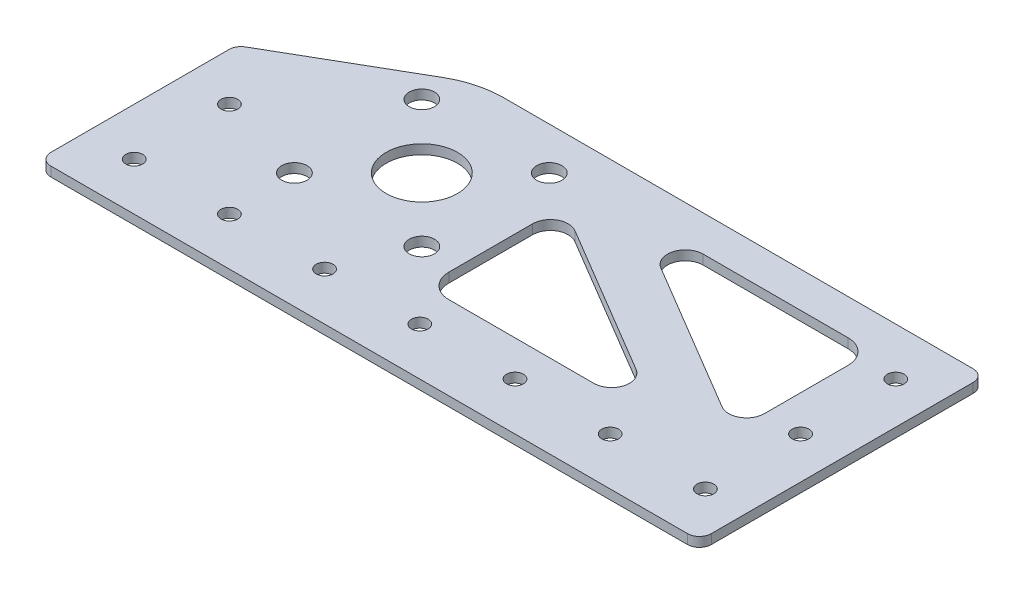
SolidWorks part; units mm, degrees
material "6061-O (SS)"
ref_plane "Front Plane" through (0, 0, 0) normal (0, 0, 1) x (1, 0, 0)
ref_plane "Top Plane" through (0, 0, 0) normal (0, 1, 0) x (1, 0, 0)
ref_plane "Right Plane" through (0, 0, 0) normal (1, 0, 0) x (0, 0, -1)
sketch "Sketch1" plane through (0, 0, 0) normal (0, 1, 0) x (1, 0, 0)
  line L2 (0, 50.7261) -> (0, 3.175)
  line L3 (3.175, 0) -> (173.0375, 0)
  line L4 (176.2125, 73.025) -> (176.2125, 3.175)
  line L8 (173.0375, 76.2) -> (47.7531, 76.2)
  line L13 (0, 787.4) -> (0, 25.4) construction
  line L14 (-76.2, 0) -> (609.6, 0) construction
  line L18 (177.8, 787.4) -> (177.8, 25.4) construction
  line L19 (1.5875, 53.4757) -> (35.0531, 72.797)
  arc A3 (165.0238, 65.5687) -> (165.0238, 61.4313) centre (165.1, 63.5) ccw construction
  arc A4 (0, 3.175) -> (3.175, 0) centre (3.175, 3.175) ccw
  arc A5 (1.5875, 53.4757) -> (0, 50.7261) centre (3.175, 50.7261) ccw
  arc A8 (173.0375, 76.2) -> (176.2125, 73.025) centre (173.0375, 73.025) cw
  arc A9 (173.0375, 0) -> (176.2125, 3.175) centre (173.0375, 3.175) ccw
  arc A12 (35.0531, 72.797) -> (47.7531, 76.2) centre (47.7531, 50.8) cw
  circle A13 centre (37.25, 64.9) radius 7.9375 construction
  arc A14 (40.425, 64.9) -> (39.4951, 62.6549) centre (37.25, 64.9) ccw construction
  dimension "D2" = 12.7
  dimension "D5" = 30
  dimension "D3" = 1.5875
  dimension "D4" = 3.175
  dimension "D1" = 15.875
  dimension "D6" = 25.4
extrude "Boss-Extrude1" add sketch "Sketch1" along normal blind 2.54 contours L4 A9 L3 A4 L2 A5 L19 A12 L8 A8
hole_wizard "#8 Clearance Hole1" positions "Sketch2" profile "Sketch3" hole size "#8" standard "ANSI Inch" end condition through all
sketch "Sketch2" plane through (0, 2.54, 0) normal (0, 1, 0) x (1, 0, 0)
  arc A0 (141.7687, 12.7762) -> (137.6313, 12.7762) centre (139.7, 12.7) ccw construction
  arc A1 (163.0313, 12.6238) -> (167.1687, 12.6238) centre (165.1, 12.7) ccw construction
  point P0 (12.7, 12.7)
  point P2 (38.1, 12.7)
  point P6 (88.9, 12.7)
  point P8 (63.5, 12.7)
  point P10 (114.3, 12.7)
  point P12 (139.7, 12.7)
  point P14 (165.1, 12.7)
  point P16 (165.1, 63.5)
  point P18 (165.1, 38.1)
  point P20 (12.7, 38.1)
  point P24 (0, 0)
  point P28 (0, 0)
  point P32 (-55.3163, -28.5057)
  point P34 (-80.7163, -28.5057)
  point P36 (-106.1163, -28.5057)
  point P38 (-131.5163, -28.5057)
  point P40 (-156.9163, -28.5057)
  point P42 (-156.9163, -3.1057)
  point P44 (-4.4768, -3.1057)
  point P45 (-4.5163, -3.1057)
  point P47 (-4.5163, 22.2943)
sketch "Sketch3" plane through (12.7, 2.54, -12.7) normal (1, 0, 0) x (0, 0, 1)
  line L0 (0, 0) -> (0, 2.54)
  line L1 (0, 2.54) -> (2.2479, 2.54)
  line L2 (2.2479, 2.54) -> (2.2479, 0)
  line L5 (2.2479, 0) -> (0, 0)
  line L11 (0, -6.35) -> (0, 107.95) construction
  dimension "Thru Hole Dia." = 4.4958
  dimension "Thru Hole Depth" = 2.54
hole_wizard "1/4 Clearance Hole1" positions "Sketch4" profile "Sketch5" hole size "1/4" standard "ANSI Inch" end condition through all
sketch "Sketch4" plane through (0, 2.54, 0) normal (0, 1, 0) x (1, 0, 0)
  point P0 (37.25, 30.9)
  point P2 (37.25, 64.9)
  point P4 (71.25, 64.9)
  point P6 (71.25, 30.9)
sketch "Sketch5" plane through (37.25, 2.54, -30.9) normal (1, 0, 0) x (0, 0, 1)
  line L0 (0, 0) -> (0, 2.54)
  line L1 (0, 2.54) -> (3.3782, 2.54)
  line L2 (3.3782, 2.54) -> (3.3782, 0)
  line L5 (3.3782, 0) -> (0, 0)
  line L11 (0, -6.35) -> (0, 107.95) construction
  dimension "Thru Hole Dia." = 6.7564
  dimension "Thru Hole Depth" = 2.54
sketch "Sketch6" plane through (0, 0, 0) normal (0, -1, 0) x (1, 0, 0)
  line L1 (149.225, -66.675) -> (110.5419, -66.675)
  line L2 (155.575, -60.325) -> (155.575, -37.9817)
  line L3 (125.8081, -22.225) -> (87.125, -22.225)
  line L4 (80.775, -50.9183) -> (80.775, -28.575)
  line L9 (173.0375, -76.2) -> (47.7531, -76.2) construction
  line L10 (155.575, -22.225) -> (80.775, -66.675) construction
  line L11 (128.241, -31.0817) -> (87.9705, -55.0125)
  line L12 (148.3795, -33.8875) -> (108.109, -57.8183)
  line L13 (158.8189, -27.6839) -> (84.0189, -72.1339) construction
  line L14 (152.3311, -16.7661) -> (77.5311, -61.2161) construction
  circle A1 centre (54.25, -47.9) radius 9.525
  circle A9 centre (165.1, -38.1) radius 2.2479 construction
  circle A10 centre (139.7, -12.7) radius 2.2479 construction
  circle A11 centre (71.25, -30.9) radius 3.3782 construction
  arc A12 (87.125, -22.225) -> (80.775, -28.575) centre (87.125, -28.575) ccw
  arc A13 (149.225, -66.675) -> (155.575, -60.325) centre (149.225, -60.325) ccw
  arc A14 (110.5419, -66.675) -> (108.109, -57.8183) centre (110.5419, -61.9125) cw
  arc A15 (148.3795, -33.8875) -> (155.575, -37.9817) centre (150.8125, -37.9817) cw
  arc A16 (80.775, -50.9183) -> (87.9705, -55.0125) centre (85.5375, -50.9183) ccw
  arc A17 (125.8081, -22.225) -> (128.241, -31.0817) centre (125.8081, -26.9875) cw
  point P43 (0, 0)
  point P44 (0, 0)
  point P45 (0, 0)
  point P46 (0, 0)
  dimension "D1" = 19.05
  dimension "D14" = 6.35
  dimension "D15" = 4.7625
  dimension "D8" = 9.525
  dimension "D9" = 9.525
  dimension "D10" = 9.525
  dimension "D11" = 9.525
  dimension "D12" = 6.35
  dimension "D13" = 6.35
extrude "Cut-Extrude1" cut sketch "Sketch6" against normal through all
